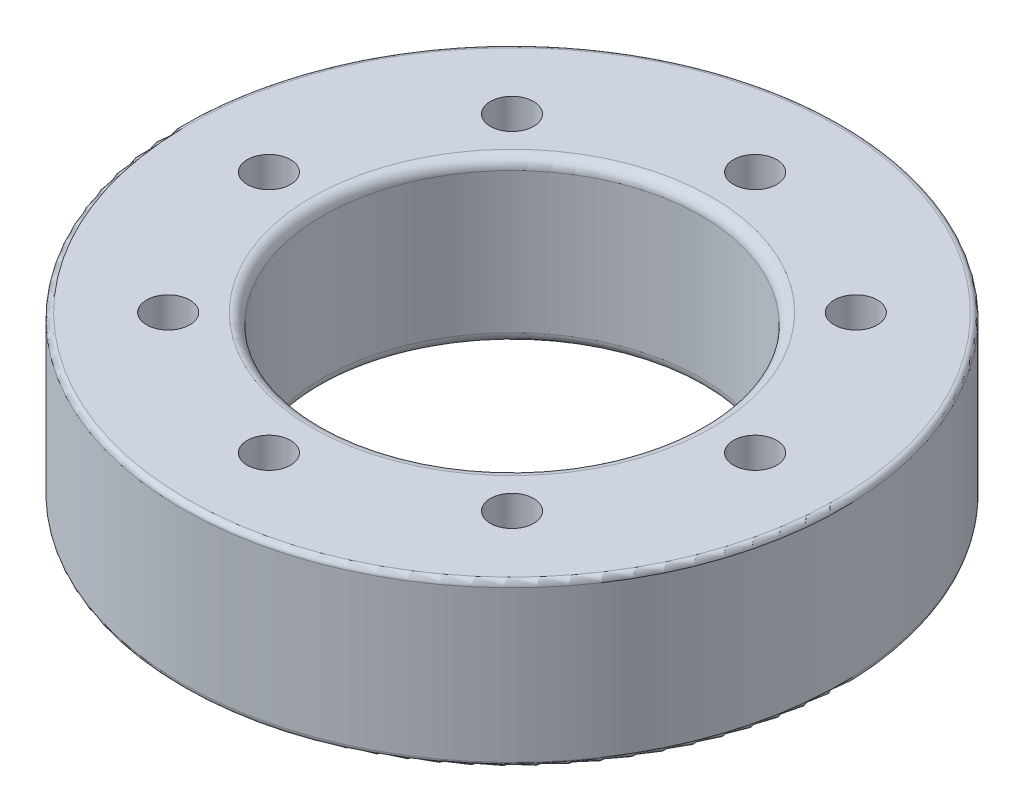
SolidWorks part; units mm, degrees
ref_plane "Front Plane" through (0, 0, 0) normal (0, 0, 1) x (1, 0, 0)
ref_plane "Top Plane" through (0, 0, 0) normal (0, 1, 0) x (1, 0, 0)
ref_plane "Right Plane" through (0, 0, 0) normal (1, 0, 0) x (0, 0, -1)
sketch "Sketch1" plane through (0, 0, 0) normal (0, 1, 0) x (1, 0, 0)
  circle A0 centre (0, 0) radius 30.5
  circle A1 centre (0, 0) radius 17.5
  dimension "D1" = 61
  dimension "D2" = 35
extrude "Boss-Extrude1" add sketch "Sketch1" along normal blind 15
sketch "Sketch2" plane through (0, 15, 0) normal (0, 1, 0) x (1, 0, 0)
  circle A0 centre (0, 0) radius 22.5 construction
  circle A1 centre (0, 22.5) radius 2
  circle A2 centre (15.9099, 15.9099) radius 2
  circle A3 centre (22.5, 0) radius 2
  circle A4 centre (15.9099, -15.9099) radius 2
  circle A5 centre (0, -22.5) radius 2
  circle A6 centre (-15.9099, -15.9099) radius 2
  circle A7 centre (-22.5, 0) radius 2
  circle A8 centre (-15.9099, 15.9099) radius 2
  point P22 (0, 0)
  dimension "D1" = 45
  dimension "D3" = 4
  dimension "D2" = 8
extrude "Cut-Extrude1" cut sketch "Sketch2" against normal blind 15
fillet "Fillet1" radius 1 2 edges at (0, 0, 17.5) (0, 15, 17.5)
fillet "Fillet2" radius 0.5 2 edges at (0, 0, 30.5) (0, 15, 30.5)
